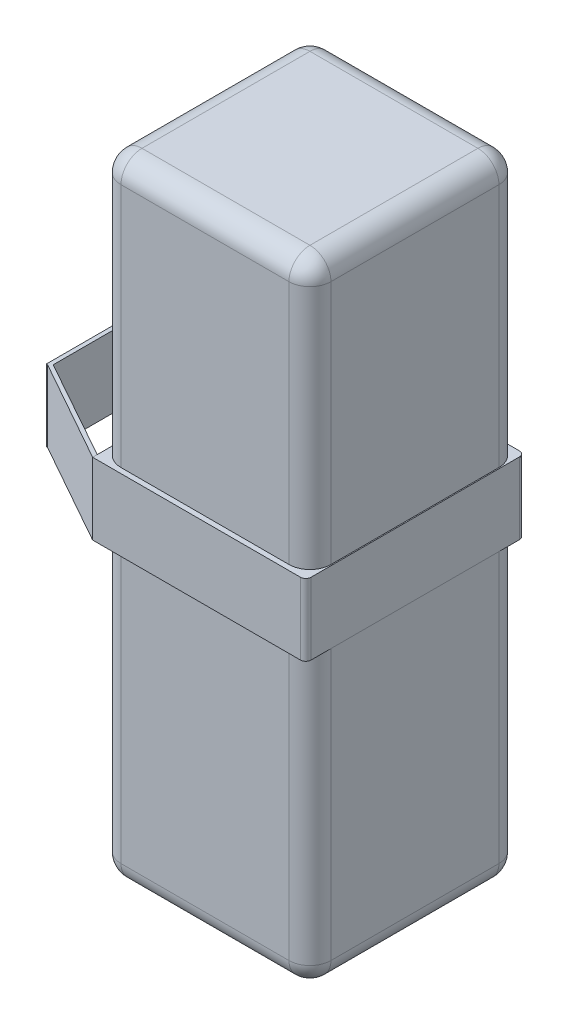
SolidWorks part; units mm, degrees
material "陶瓷"
ref_plane "前视基准面" through (0, 0, 0) normal (0, 0, 1) x (1, 0, 0)
ref_plane "上视基准面" through (0, 0, 0) normal (0, 1, 0) x (1, 0, 0)
ref_plane "右视基准面" through (0, 0, 0) normal (1, 0, 0) x (0, 0, -1)
other "Configuration Table"
sketch "草图1" plane through (0, 0, 0) normal (1, 0, 0) x (0, 0, -1)
  line L1 (-10, -30) -> (10, -30)
  line L2 (-10, -30) -> (-10, 30)
  line L3 (-10, 30) -> (10, 30)
  line L4 (10, -30) -> (10, 30)
  line L5 (-10, -30) -> (10, 30) construction
  line L6 (-10, 30) -> (10, -30) construction
  point P0 (0, 0)
extrude "凸台-拉伸1" add sketch "草图1" along normal blind 20
fillet "圆角1" radius 2 12 edges at (10, 30, -10) (10, 30, 10) (10, -30, 10) (10, -30, -10) (20, -30, 0) (20, 0, 10) (20, 30, 0) (20, 0, -10) (0, -30, 0) (0, 0, 10) (0, 30, 0) (0, 0, -10)
sketch "草图2" plane through (0, 0, 10) normal (0, 0, 1) x (1, 0, 0)
  line L0 (2, 0) -> (18, 0)
  line L1 (2, 28) -> (2, -28) construction
  line L2 (18, -28) -> (18, 28) construction
  line L3 (2, 0) -> (2, 1.1559)
  line L4 (2, 1.1559) -> (18, 1.1559)
  line L5 (18, 1.1559) -> (18, 0)
extrude "凸台-拉伸2" add sketch "草图2" along normal blind 0.5
sketch "草图3" plane through (18, 0, 0) normal (1, 0, 0) x (0, 0, -1)
  line L0 (-10.5, 1.1559) -> (-10.5, 4.6672)
  line L1 (-10.5, 4.6672) -> (10.351, 4.6672)
  line L2 (10.351, 4.6672) -> (10.351, -2.1665)
  line L3 (10.351, -2.1665) -> (-10.5, -2.1665)
  line L4 (-10.5, -2.1665) -> (-10.5, 1.1559)
extrude "凸台-拉伸3" add sketch "草图3" along normal blind 2.1 and the other way blind 18.2 contours L4 L0 L1 L2 L3
sketch "草图4" plane through (0, 0, 0) normal (-1, 0, 0) x (0, 0, 1)
  line L0 (0, 4.6672) -> (-5, 4.6672)
  line L1 (-8, 4.6672) -> (8, 4.6672) construction
  line L2 (-5, 4.6672) -> (-5, 6.6714)
  line L3 (-5, 6.6714) -> (-5.4769, 6.6714)
  line L4 (-5.4769, 6.6714) -> (-5.4769, 4.6672)
  line L5 (-5.4769, 4.6672) -> (-5, 4.6672)
  line L6 (0, 4.6672) -> (5, 4.6672)
  line L7 (5, 4.6672) -> (5, 6.6714)
  line L8 (5, 6.6714) -> (5.4246, 6.6714)
  line L9 (5.4246, 6.6714) -> (5.4246, 4.6672)
  line L10 (5.4246, 4.6672) -> (5, 4.6672)
extrude "凸台-拉伸4" add sketch "草图4" along normal blind 0.1 contours L2 L3 L4 L5 | L7 L8 L9 L10
sketch "草图5" plane through (0, -2.1665, 0) normal (0, -1, 0) x (1, 0, 0)
  line L0 (0, 8) -> (-10, 8)
  line L1 (-10, 8) -> (-10, 0)
  line L2 (-10, 0) -> (-10, 5)
  line L3 (-10, 5) -> (-10, -6.1711)
  line L4 (-0.2, 10.5) -> (-10, 5)
  line L5 (-10, -6.1711) -> (-0.2, -10.351)
  line L6 (-0.2, -10.351) -> (20.1, -10.351) construction
  line L7 (-0.2, -10.351) -> (-0.2, 10.5) construction
  line L8 (-0.2, -10.351) -> (-0.2, 10.5)
  line M12 (-0.2, 10.5) -> (-0.2, -10.351)
extrude "凸台-拉伸5" add sketch "草图5" against normal blind 6.83 contours L3 L5 L0 L4 L1 M12 | L4 L0 M12
sketch "草图6" plane through (0, -2.1665, 0) normal (0, -1, 0) x (1, 0, 0)
  line L0 (-0.2, 10.5) -> (-0.2, 10.0626)
  line L1 (-0.2, 10.0626) -> (-9.7077, 4.7493)
  line L2 (-9.7077, 4.7493) -> (-9.7077, -5.8773)
  line L3 (-9.7077, -5.8773) -> (-0.2, -10.0732)
  line L4 (-0.2, -10.0732) -> (-0.2, 10.0626)
  line L5 (-0.2, 10.0626) -> (-0.2, -10.0732)
extrude "切除-拉伸1" cut sketch "草图6" against normal blind 6.83 contours L3 L4 L1 L2
sketch "草图7" plane through (-10, 0, 0) normal (-1, 0, 0) x (0, 0, 1)
  line L0 (-6.1711, 4.6635) -> (5, 4.6635)
  line L1 (5, 4.6635) -> (5, -2.1665)
  line L2 (5, -2.1665) -> (-6.1711, -2.1665)
  line L3 (-6.1711, -2.1665) -> (-6.1711, 4.6635)
extrude "凸台-拉伸6" add sketch "草图7" along normal blind 0.1
fillet "圆角5" radius 0.5 2 edges at (20.1, 1.2503, -10.351) (20.1, 1.2503, 10.5)
